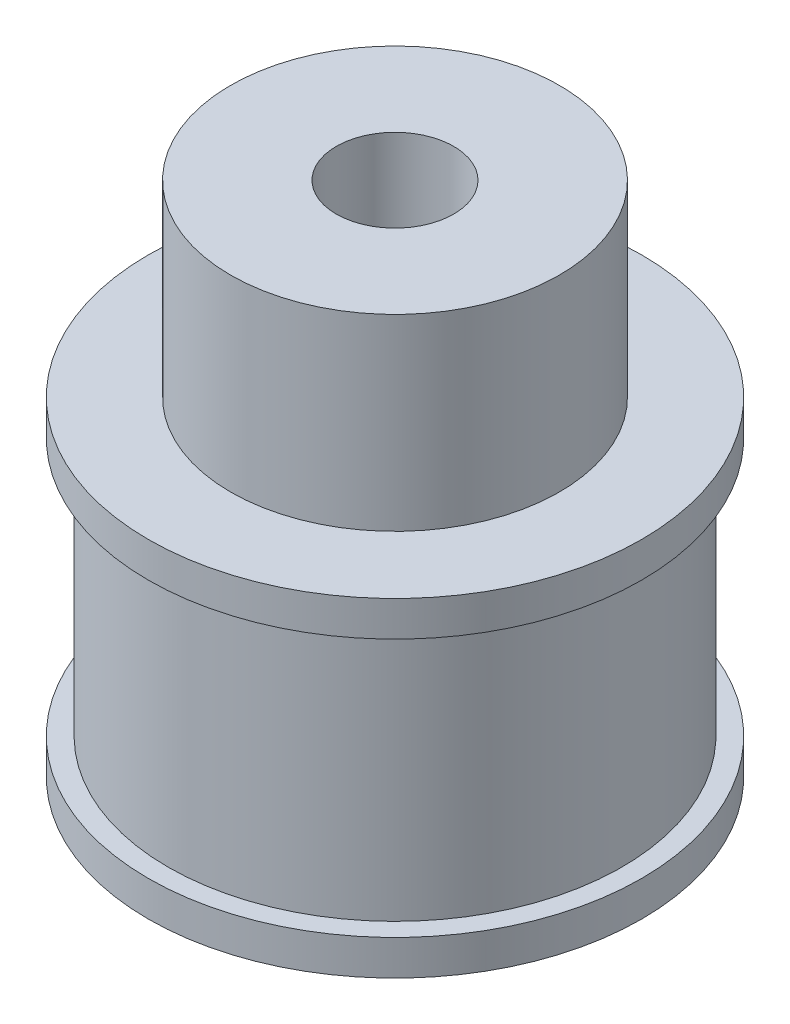
SolidWorks part; units mm, degrees
ref_plane "Front Plane" through (0, 0, 0) normal (0, 0, 1) x (1, 0, 0)
ref_plane "Top Plane" through (0, 0, 0) normal (0, 1, 0) x (1, 0, 0)
ref_plane "Right Plane" through (0, 0, 0) normal (1, 0, 0) x (0, 0, -1)
sketch "Sketch1" plane through (0, 0, 0) normal (0, 1, 0) x (1, 0, 0)
  circle A0 centre (0, 0) radius 10.5
  dimension "D1" = 21
extrude "Boss-Extrude1" add sketch "Sketch1" along normal blind 14
sketch "Sketch2" plane through (0, 14, 0) normal (0, 1, 0) x (1, 0, 0)
  circle A0 centre (0, 0) radius 7
  dimension "D1" = 14
extrude "Boss-Extrude2" add sketch "Sketch2" along normal blind 8
sketch "Sketch3" plane through (0, 22, 0) normal (0, 1, 0) x (1, 0, 0)
  circle A0 centre (0, 0) radius 2.5
  dimension "D1" = 5
extrude "Cut-Extrude1" cut sketch "Sketch3" against normal through all
sketch "Sketch4" plane through (0, 0, 0) normal (0, 1, 0) x (1, 0, 0)
  circle A0 centre (0, 0) radius 9.6623
extrude "Cut-Extrude2" cut sketch "Sketch4" along normal blind 11 from offset 1.5 flip side to cut
